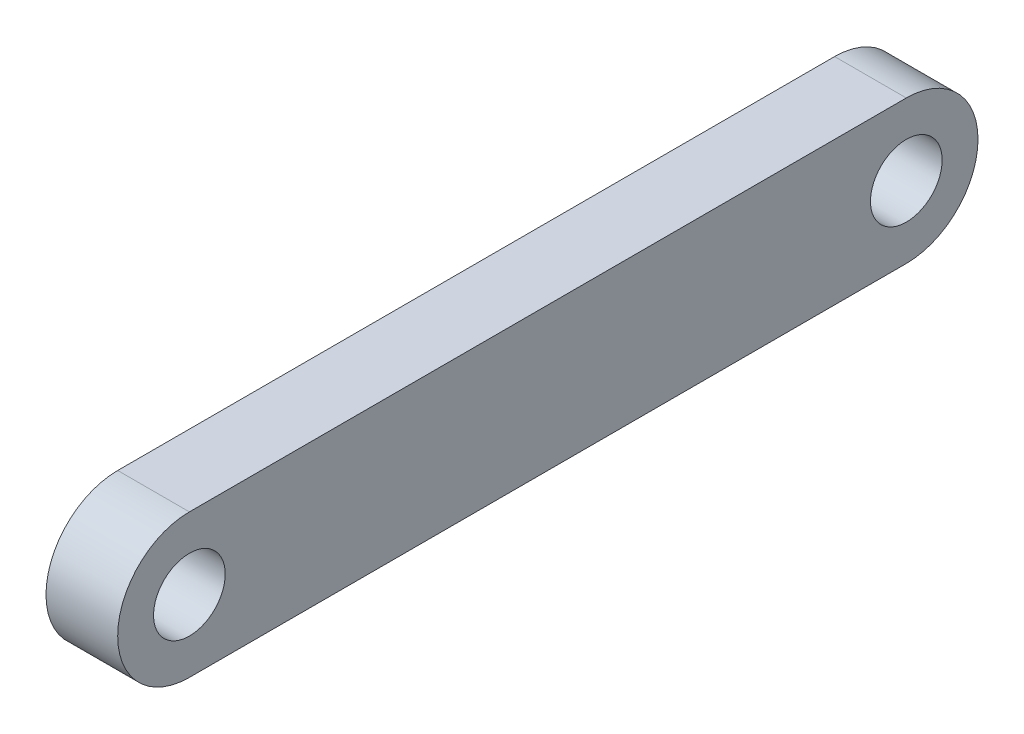
SolidWorks part; units mm, degrees
material "6061-T6 (SS)"
ref_plane "Front Plane" through (0, 0, 0) normal (0, 0, 1) x (1, 0, 0)
ref_plane "Top Plane" through (0, 0, 0) normal (0, 1, 0) x (1, 0, 0)
ref_plane "Right Plane" through (0, 0, 0) normal (1, 0, 0) x (0, 0, -1)
sketch "Sketch1" plane through (0, 0, 0) normal (1, 0, 0) x (0, 0, -1)
  line L0 (0, 100) -> (1000, 100)
  line L1 (1000, -100) -> (0, -100)
  line L2 (0, 0) -> (1000, 0) construction
  circle A0 centre (0, 0) radius 50
  circle A1 centre (1000, 0) radius 50
  arc A2 (1000, 100) -> (1000, -100) centre (1000, 0) cw
  arc A3 (0, -100) -> (0, 100) centre (0, 0) cw
  dimension "D2" = 100
  dimension "D3" = 100
  dimension "D1" = 1000
extrude "Boss-Extrude1" add sketch "Sketch1" along normal blind 100
